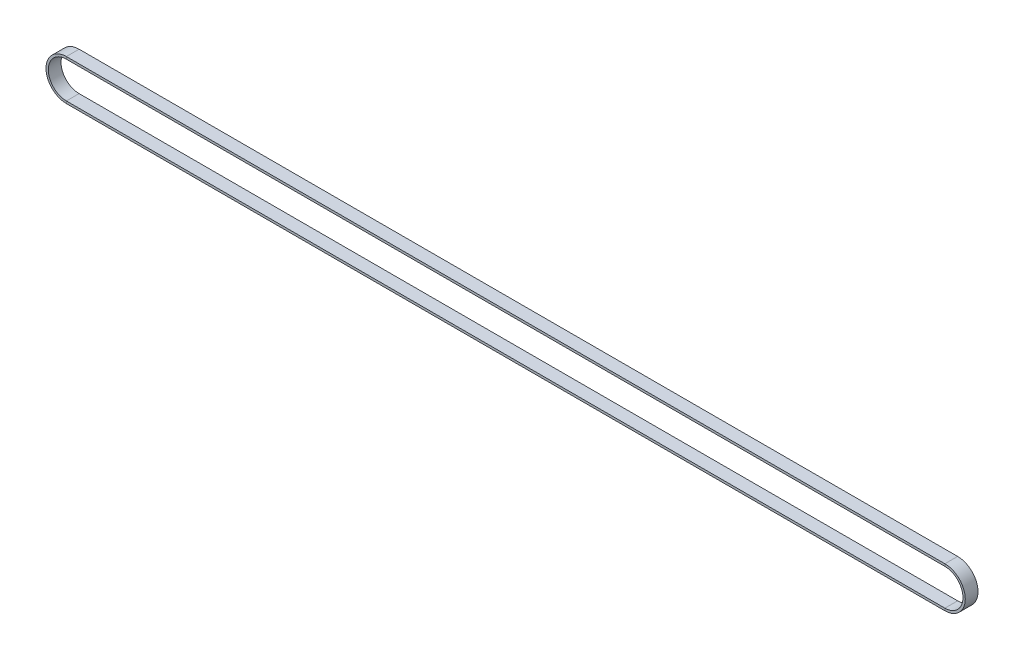
SolidWorks part; units mm, degrees
ref_plane "Front Plane" through (0, 0, 0) normal (0, 0, 1) x (1, 0, 0)
ref_plane "Top Plane" through (0, 0, 0) normal (0, 1, 0) x (1, 0, 0)
ref_plane "Right Plane" through (0, 0, 0) normal (1, 0, 0) x (0, 0, -1)
sketch "Sketch2" plane through (0, 0, 0) normal (0, 0, 1) x (1, 0, 0)
  line L2 (0, 10.16) -> (438.15, 10.16)
  line L3 (438.15, -10.16) -> (0, -10.16)
  arc A0 (0, -10.16) -> (0, 10.16) centre (0, 0) cw
  arc A1 (438.15, 10.16) -> (438.15, -10.16) centre (438.15, 0) cw
  point P0 (457.2, -10.16)
  point P9 (0, 0)
  dimension "D1" = 10.16
  dimension "D2" = 438.15
ref_plane "Plane1" through (0, 0, 0) normal (0, 0, 1) x (1, 0, 0)
ref_plane "Plane2" through (0, 10.16, 0) normal (1, 0, 0) x (0, 0, -1)
sketch "Sketch3" plane through (0, 10.16, 0) normal (1, 0, 0) x (0, 0, -1)
  line L0 (0, 0) -> (0, -1.143) construction
  line L1 (0, 0) -> (0, -20.32) construction
  line L2 (0, 0) -> (0, -20.32) construction
  line L3 (-3.175, -1.143) -> (3.175, -1.143)
  line L4 (3.175, -1.143) -> (3.175, 0)
  line L5 (3.175, 0) -> (-3.175, 0)
  line L6 (-3.175, -1.143) -> (-3.175, 0)
  dimension "D1" = 6.35
  dimension "D2" = 1.143
sweep "Sweep1" add profiles "Sketch3" path "Sketch2"
